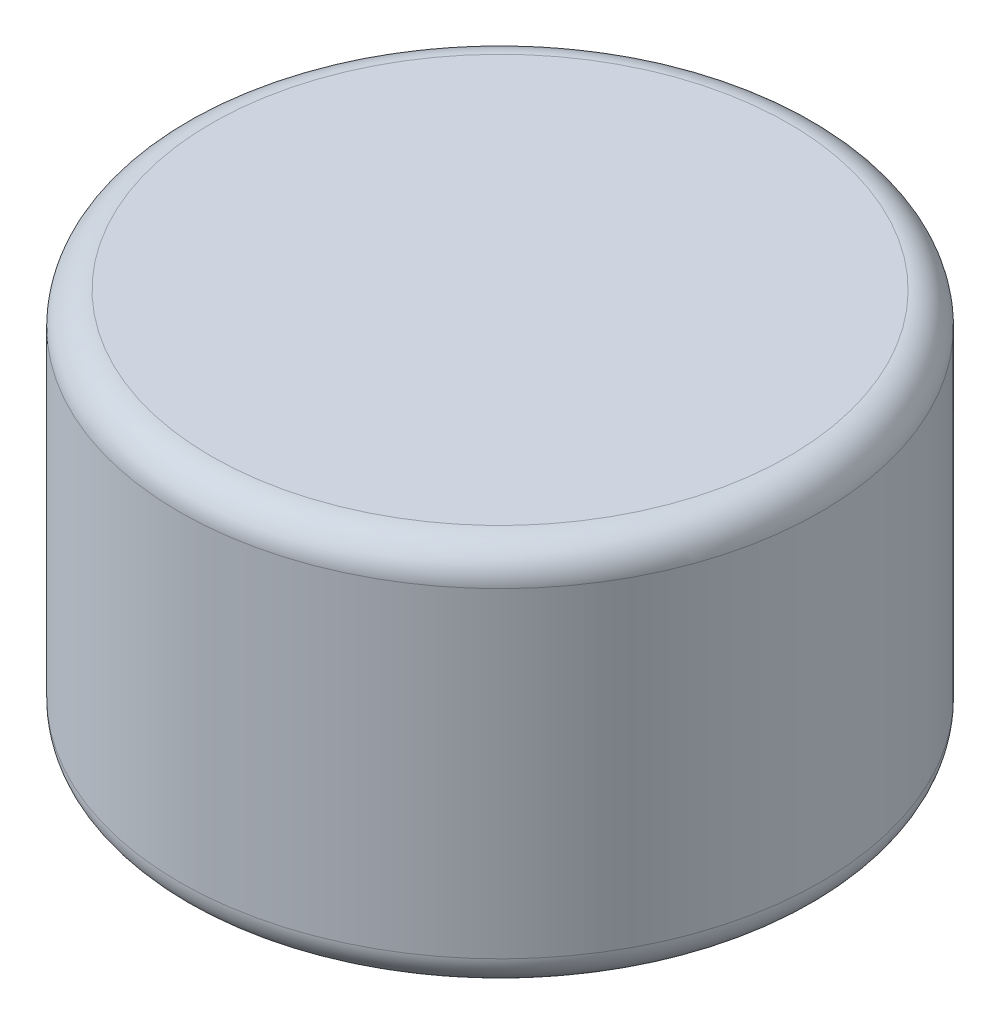
SolidWorks part; units mm, degrees
material "STAINLESS STEEL, 304"
ref_plane "Front Plane" through (0, 0, 0) normal (0, 0, 1) x (1, 0, 0)
ref_plane "Top Plane" through (0, 0, 0) normal (0, 1, 0) x (1, 0, 0)
ref_plane "Right Plane" through (0, 0, 0) normal (1, 0, 0) x (0, 0, -1)
sketch "Sketch1" plane through (0, 0, 0) normal (0, 1, 0) x (1, 0, 0)
  circle A0 centre (0, 0) radius 2.5
  dimension "D1" = 5
extrude "Boss-Extrude1" add sketch "Sketch1" along normal blind 3
fillet "Fillet1" radius 0.25 2 edges at (0, 0, 2.5) (0, 3, 2.5)
